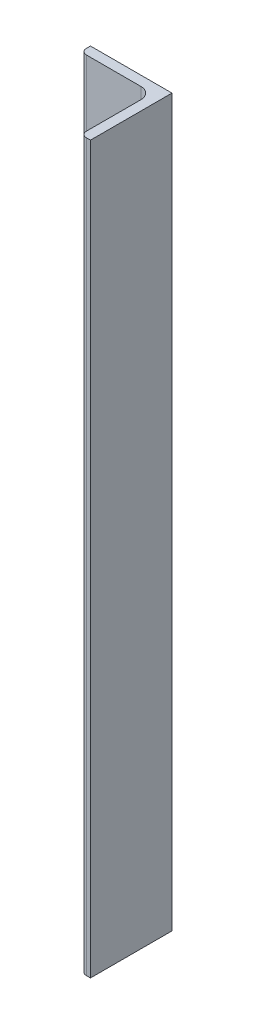
SolidWorks part; units mm, degrees
ref_plane "Front Plane" through (0, 0, 0) normal (0, 0, 1) x (1, 0, 0)
ref_plane "Top Plane" through (0, 0, 0) normal (0, 1, 0) x (1, 0, 0)
ref_plane "Right Plane" through (0, 0, 0) normal (1, 0, 0) x (0, 0, -1)
sketch "Sketch1" plane through (0, 0, 0) normal (0, 1, 0) x (1, 0, 0)
  line L6 (0, 0) -> (-50, 0)
  line L10 (0, 0) -> (0, -50)
  line L11 (0, -50) -> (-2.5, -50)
  line L12 (-50, 0) -> (-50, -2.5)
  line L15 (-46.5, -6) -> (-13, -6)
  line L16 (-6, -46.5) -> (-6, -13)
  arc A8 (-13, -6) -> (-6, -13) centre (-13, -13) cw
  arc A9 (-2.5, -50) -> (-6, -46.5) centre (-2.5, -46.5) cw
  arc A10 (-50, -2.5) -> (-46.5, -6) centre (-46.5, -2.5) ccw
  dimension "D4" = 6
  dimension "D5" = 7
  dimension "D6" = 3.5
  dimension "D1" = 50
  dimension "D2" = 50
  dimension "D3" = 6
extrude "Boss-Extrude1" add sketch "Sketch1" along normal mid plane 445
